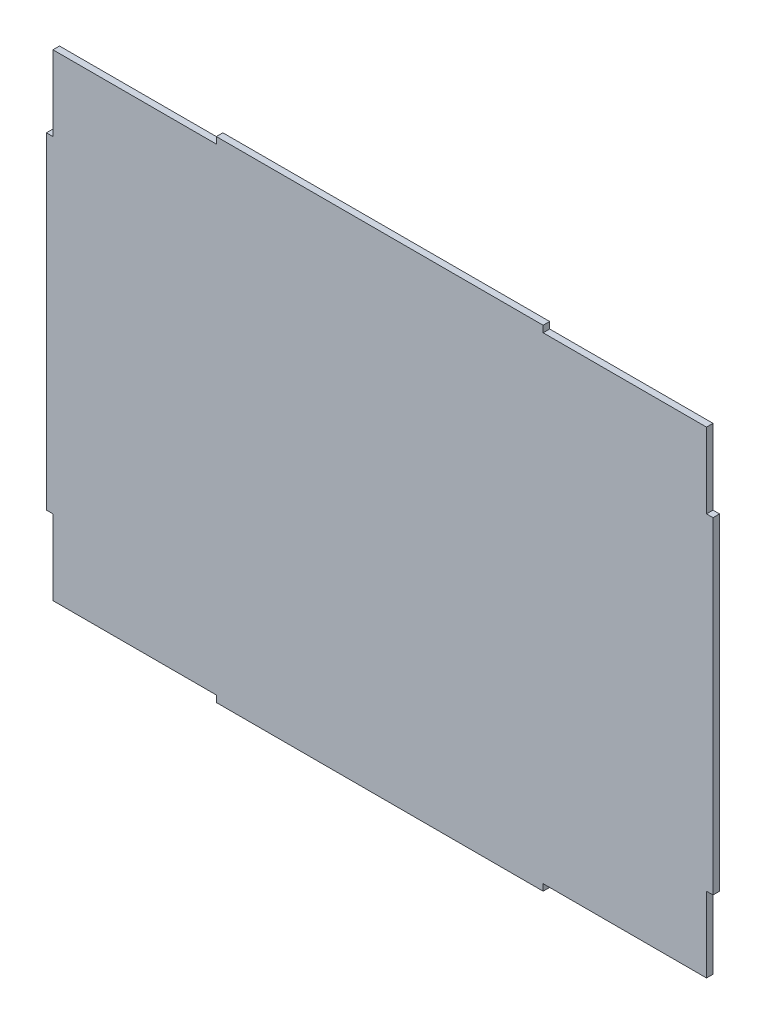
SolidWorks part; units mm, degrees
ref_plane "Front Plane" through (0, 0, 0) normal (0, 0, 1) x (1, 0, 0)
ref_plane "Top Plane" through (0, 0, 0) normal (0, 1, 0) x (1, 0, 0)
ref_plane "Right Plane" through (0, 0, 0) normal (1, 0, 0) x (0, 0, -1)
sketch "Sketch1" plane through (0, 0, 0) normal (0, 0, 1) x (1, 0, 0)
  line L0 (0, 0) -> (0, -23)
  line L1 (0, -23) -> (-2, -23)
  line L2 (-2, -23) -> (-2, -123)
  line L8 (0, 0) -> (50, 0)
  line L13 (-2, -123) -> (0, -123)
  line L14 (0, -123) -> (0, -146)
  line L15 (0, -146) -> (50, -146)
  line L22 (50, -146) -> (50, -148)
  line L23 (50, -148) -> (100, -148)
  line L25 (100, 2) -> (50, 2)
  line L26 (50, 2) -> (50, 0)
  line L27 (100, -148) -> (100, 2)
  dimension "D1" = 2
  dimension "D2" = 23
  dimension "D3" = 100
  dimension "D4" = 2
  dimension "D5" = 2
  dimension "D6" = 50
  dimension "D7" = 23
  dimension "D8" = 50
extrude "Boss-Extrude1" add sketch "Sketch1" along normal blind 2
mirror "Mirror2" about plane through (100, -148, 2) normal (-1, 0, 0) of "Boss-Extrude1"
